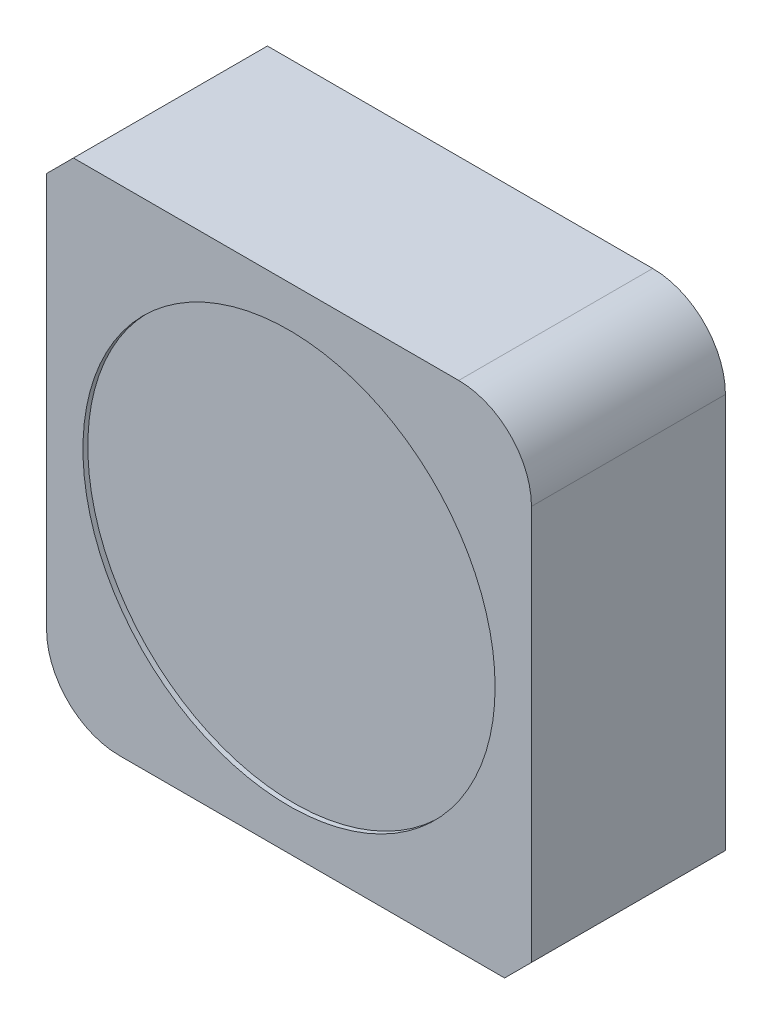
SolidWorks part; units mm, degrees
ref_plane "Спереди" through (0, 0, 0) normal (0, 0, 1) x (1, 0, 0)
ref_plane "Сверху" through (0, 0, 0) normal (0, 1, 0) x (1, 0, 0)
ref_plane "Справа" through (0, 0, 0) normal (1, 0, 0) x (0, 0, -1)
sketch "Эскиз1" plane through (0, 0, 0) normal (0, 0, 1) x (1, 0, 0)
  line L8 (-5, 4.5459) -> (-5, -5.1)
  line L17 (-5, -5.1) -> (4.4459, -5.1)
  line L18 (4.4459, -5.1) -> (5, -4.5459)
  line L19 (5, -4.5459) -> (5, 5.1)
  line L20 (5, 5.1) -> (-4.4459, 5.1)
  line L21 (-4.4459, 5.1) -> (-5, 4.5459)
  line L22 (-5, 4.5459) -> (5, -4.5459) construction
  point P6 (0, 0)
  dimension "D1" = 135
  dimension "D2" = 10.2
  dimension "D3" = 10
  dimension "D4" = 13.5
extrude "Бобышка-Вытянуть1" add sketch "Эскиз1" along normal blind 4
fillet "Скругление1" radius 1.5 2 edges at (5, 5.1, 2) (-5, -5.1, 2)
sketch "Эскиз2" plane through (0, 0, 4) normal (0, 0, 1) x (1, 0, 0)
  circle A0 centre (0, 0) radius 4.25
  dimension "D1" = 8.5
extrude "Вырез-Вытянуть1" cut sketch "Эскиз2" against normal blind 0.1
